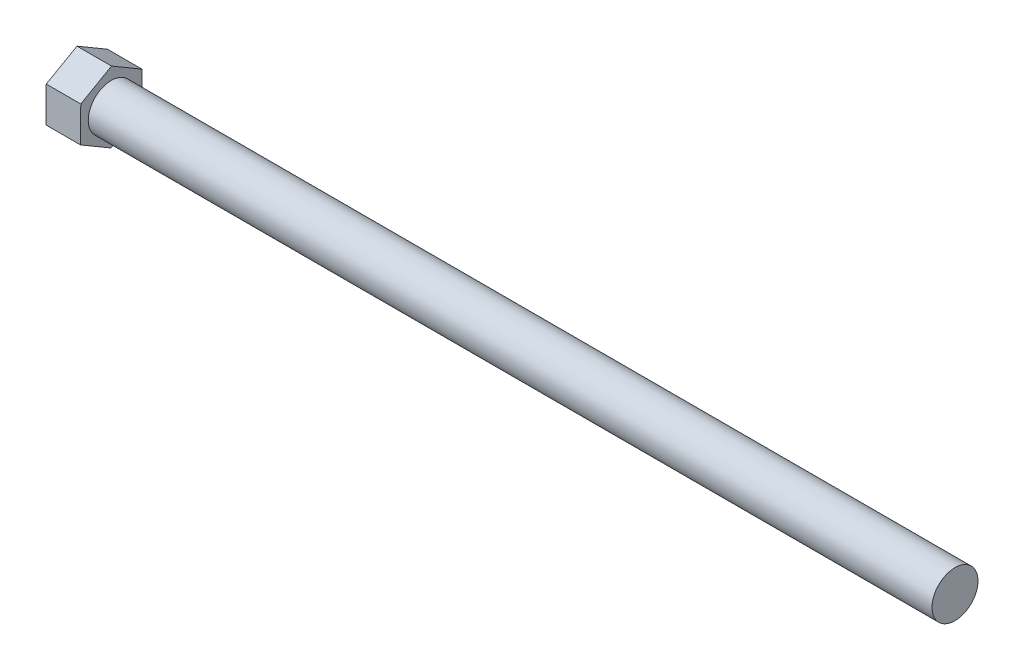
SolidWorks part; units mm, degrees
ref_plane "Спереди" through (0, 0, 0) normal (0, 0, 1) x (1, 0, 0)
ref_plane "Сверху" through (0, 0, 0) normal (0, 1, 0) x (1, 0, 0)
ref_plane "Справа" through (0, 0, 0) normal (1, 0, 0) x (0, 0, -1)
sketch "Эскиз1" plane through (0, 0, 0) normal (1, 0, 0) x (0, 0, -1)
  circle A0 centre (0, 0) radius 6
  dimension "D1" = 12
extrude "Бобышка-Вытянуть1" add sketch "Эскиз1" along normal blind 220
sketch "Эскиз2" plane through (0, 0, 0) normal (-1, 0, 0) x (0, 0, 1)
  line L1 (8.0144, -4.5511) -> (7.9485, 4.6651)
  line L2 (7.9485, 4.6651) -> (-0.0659, 9.2162)
  line L3 (-0.0659, 9.2162) -> (-8.0144, 4.5511)
  line L4 (-8.0144, 4.5511) -> (-7.9485, -4.6651)
  line L5 (-7.9485, -4.6651) -> (0.0659, -9.2162)
  line L6 (0.0659, -9.2162) -> (8.0144, -4.5511)
  circle A0 centre (0, 0) radius 7.9816 construction
extrude "Бобышка-Вытянуть2" add sketch "Эскиз2" along normal blind 9
